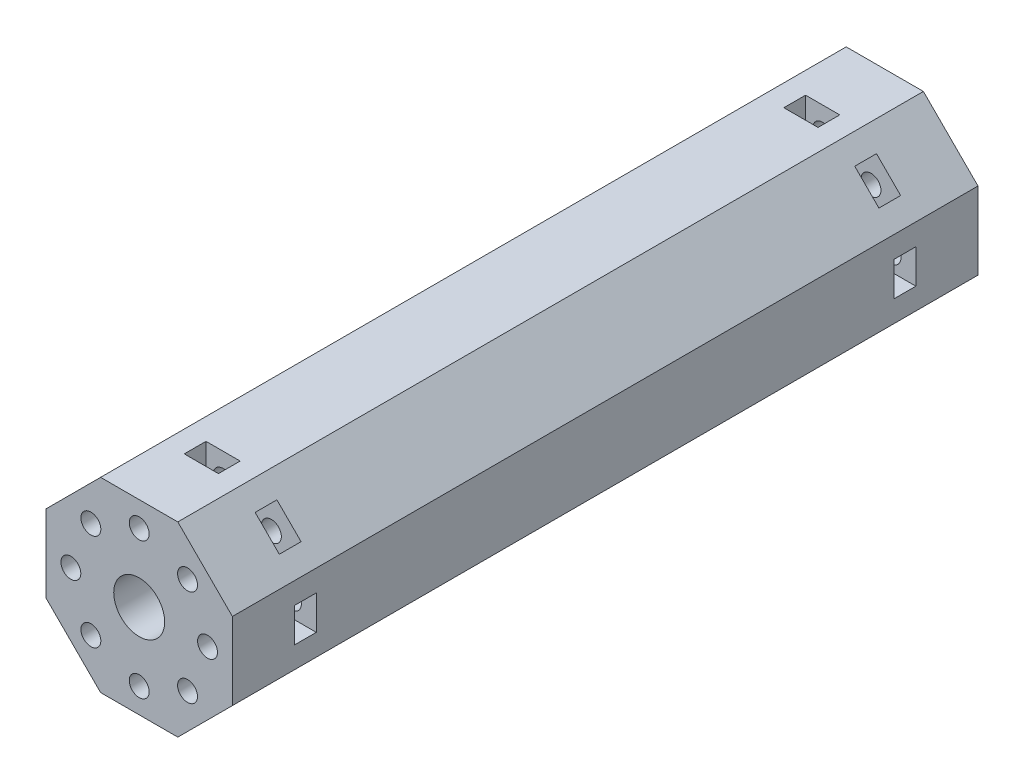
SolidWorks part; units mm, degrees
ref_plane "Alzado" through (0, 0, 0) normal (0, 0, 1) x (1, 0, 0)
ref_plane "Planta" through (0, 0, 0) normal (0, 1, 0) x (1, 0, 0)
ref_plane "Vista lateral" through (0, 0, 0) normal (1, 0, 0) x (0, 0, -1)
sketch "Croquis1" plane through (0, 0, 0) normal (0, 0, 1) x (1, 0, 0)
  line L1 (15, -6.2132) -> (15, 6.2132)
  line L2 (15, 6.2132) -> (6.2132, 15)
  line L3 (6.2132, 15) -> (-6.2132, 15)
  line L4 (-6.2132, 15) -> (-15, 6.2132)
  line L5 (-15, 6.2132) -> (-15, -6.2132)
  line L6 (-15, -6.2132) -> (-6.2132, -15)
  line L7 (-6.2132, -15) -> (6.2132, -15)
  line L8 (6.2132, -15) -> (15, -6.2132)
  circle A0 centre (0, 0) radius 15 construction
  dimension "D1" = 30
extrude "Saliente-Extruir1" add sketch "Croquis1" along normal blind 60
sketch "Croquis2" plane through (0, 0, 0) normal (0, 0, -1) x (-1, 0, 0)
  circle A0 centre (0, 11) radius 1.6
  circle A2 centre (7.7782, 7.7782) radius 1.6
  circle A3 centre (11, 0) radius 1.6
  circle A4 centre (7.7782, -7.7782) radius 1.6
  circle A5 centre (0, -11) radius 1.6
  circle A6 centre (-7.7782, -7.7782) radius 1.6
  circle A7 centre (-11, 0) radius 1.6
  circle A8 centre (-7.7782, 7.7782) radius 1.6
  point P22 (0, 0)
  dimension "D1" = 3.2
  dimension "D2" = 11
  dimension "D4" = 8
extrude "Cortar-Extruir1" cut sketch "Croquis2" against normal blind 20
sketch "Croquis3" plane through (0, 0, 0) normal (0, 0, -1) x (-1, 0, 0)
  line L0 (-2.75, 12.5877) -> (-2.75, 18.4632)
  line L1 (2.75, 12.5877) -> (0, 14.1754) construction
  line L2 (0, 14.1754) -> (-2.75, 12.5877) construction
  line L3 (-2.75, 12.5877) -> (-2.75, 9.4123)
  line L4 (-2.75, 9.4123) -> (0, 7.8246)
  line L5 (0, 7.8246) -> (2.75, 9.4123)
  line L6 (2.75, 9.4123) -> (2.75, 12.5877)
  line L7 (-15, 6.2132) -> (-6.2132, 15) construction
  line L8 (-2.75, 18.4632) -> (2.75, 23.9632)
  line L9 (2.75, 23.9632) -> (2.75, 12.5877)
  line L10 (6.9563, 10.8454) -> (11.1109, 15)
  line L11 (6.9563, 10.8454) -> (4.7109, 8.6)
  line L12 (4.7109, 8.6) -> (5.5328, 5.5328)
  line L13 (5.5328, 5.5328) -> (8.6, 4.7109)
  line L14 (8.6, 4.7109) -> (10.8454, 6.9563)
  line L15 (11.1109, 15) -> (18.8891, 15)
  line L16 (18.8891, 15) -> (10.8454, 6.9563)
  line L17 (10.8454, 6.9563) -> (10.0235, 10.0235) construction
  line L18 (10.0235, 10.0235) -> (6.9563, 10.8454) construction
  line L19 (12.5877, 2.75) -> (18.4632, 2.75)
  line L20 (12.5877, 2.75) -> (9.4123, 2.75)
  line L21 (9.4123, 2.75) -> (7.8246, 0)
  line L22 (7.8246, 0) -> (9.4123, -2.75)
  line L23 (9.4123, -2.75) -> (12.5877, -2.75)
  line L24 (18.4632, 2.75) -> (23.9632, -2.75)
  line L25 (23.9632, -2.75) -> (12.5877, -2.75)
  line L26 (12.5877, -2.75) -> (14.1754, 0) construction
  line L27 (14.1754, 0) -> (12.5877, 2.75) construction
  line L28 (10.8454, -6.9563) -> (15, -11.1109)
  line L29 (10.8454, -6.9563) -> (8.6, -4.7109)
  line L30 (8.6, -4.7109) -> (5.5328, -5.5328)
  line L31 (5.5328, -5.5328) -> (4.7109, -8.6)
  line L32 (4.7109, -8.6) -> (6.9563, -10.8454)
  line L33 (15, -11.1109) -> (15, -18.8891)
  line L34 (15, -18.8891) -> (6.9563, -10.8454)
  line L35 (6.9563, -10.8454) -> (10.0235, -10.0235) construction
  line L36 (10.0235, -10.0235) -> (10.8454, -6.9563) construction
  line L37 (2.75, -12.5877) -> (2.75, -18.4632)
  line L38 (2.75, -12.5877) -> (2.75, -9.4123)
  line L39 (2.75, -9.4123) -> (0, -7.8246)
  line L40 (0, -7.8246) -> (-2.75, -9.4123)
  line L41 (-2.75, -9.4123) -> (-2.75, -12.5877)
  line L42 (2.75, -18.4632) -> (-2.75, -23.9632)
  line L43 (-2.75, -23.9632) -> (-2.75, -12.5877)
  line L44 (-2.75, -12.5877) -> (0, -14.1754) construction
  line L45 (0, -14.1754) -> (2.75, -12.5877) construction
  line L46 (-6.9563, -10.8454) -> (-11.1109, -15)
  line L47 (-6.9563, -10.8454) -> (-4.7109, -8.6)
  line L48 (-4.7109, -8.6) -> (-5.5328, -5.5328)
  line L49 (-5.5328, -5.5328) -> (-8.6, -4.7109)
  line L50 (-8.6, -4.7109) -> (-10.8454, -6.9563)
  line L51 (-11.1109, -15) -> (-18.8891, -15)
  line L52 (-18.8891, -15) -> (-10.8454, -6.9563)
  line L53 (-10.8454, -6.9563) -> (-10.0235, -10.0235) construction
  line L54 (-10.0235, -10.0235) -> (-6.9563, -10.8454) construction
  line L55 (-12.5877, -2.75) -> (-18.4632, -2.75)
  line L56 (-12.5877, -2.75) -> (-9.4123, -2.75)
  line L57 (-9.4123, -2.75) -> (-7.8246, 0)
  line L58 (-7.8246, 0) -> (-9.4123, 2.75)
  line L59 (-9.4123, 2.75) -> (-12.5877, 2.75)
  line L60 (-18.4632, -2.75) -> (-23.9632, 2.75)
  line L61 (-23.9632, 2.75) -> (-12.5877, 2.75)
  line L62 (-12.5877, 2.75) -> (-14.1754, 0) construction
  line L63 (-14.1754, 0) -> (-12.5877, -2.75) construction
  line L64 (-10.8454, 6.9563) -> (-15, 11.1109)
  line L65 (-10.8454, 6.9563) -> (-8.6, 4.7109)
  line L66 (-8.6, 4.7109) -> (-5.5328, 5.5328)
  line L67 (-5.5328, 5.5328) -> (-4.7109, 8.6)
  line L68 (-4.7109, 8.6) -> (-6.9563, 10.8454)
  line L69 (-15, 11.1109) -> (-15, 18.8891)
  line L70 (-15, 18.8891) -> (-6.9563, 10.8454)
  line L71 (-6.9563, 10.8454) -> (-10.0235, 10.0235) construction
  line L72 (-10.0235, 10.0235) -> (-10.8454, 6.9563) construction
  circle A0 centre (0, 11) radius 2.75 construction
  circle A1 centre (7.7782, 7.7782) radius 2.75 construction
  circle A2 centre (11, 0) radius 2.75 construction
  circle A3 centre (7.7782, -7.7782) radius 2.75 construction
  circle A4 centre (0, -11) radius 2.75 construction
  circle A5 centre (-7.7782, -7.7782) radius 2.75 construction
  circle A6 centre (-11, 0) radius 2.75 construction
  circle A7 centre (-7.7782, 7.7782) radius 2.75 construction
  point P86 (0, 0)
  dimension "D1" = 5.5
  dimension "D2" = 8
extrude "Cortar-Extruir2" cut sketch "Croquis3" against normal blind 3.5 from offset 10 offset against normal yes
mirror "Simetría1" about plane through (0, 0, 60) normal (0, 0, 1) of "Cortar-Extruir2", "Saliente-Extruir1", "Cortar-Extruir1"
sketch "Croquis4" plane through (0, 0, 0) normal (0, 0, -1) x (-1, 0, 0)
  circle A0 centre (0, 0) radius 4.1
  dimension "D1" = 8.2
extrude "Cortar-Extruir3" cut sketch "Croquis4" against normal through all
